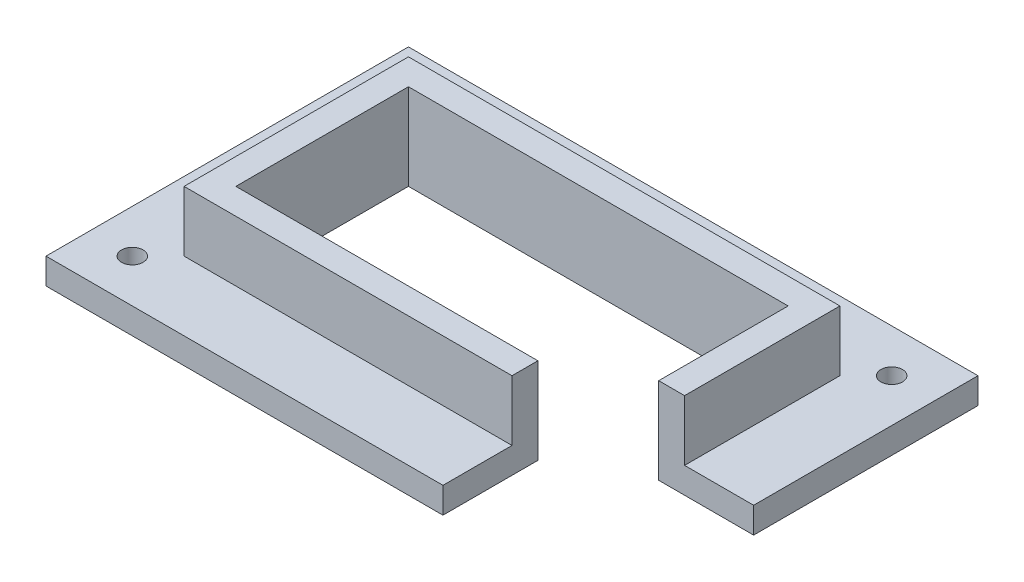
SolidWorks part; units mm, degrees
ref_plane "Front Plane" through (0, 0, 0) normal (0, 0, 1) x (1, 0, 0)
ref_plane "Top Plane" through (0, 0, 0) normal (0, 1, 0) x (1, 0, 0)
ref_plane "Right Plane" through (0, 0, 0) normal (1, 0, 0) x (0, 0, -1)
sketch "Sketch1" plane through (0, 0, 0) normal (0, 1, 0) x (1, 0, 0)
  line L0 (13, -10) -> (13, -21)
  line L1 (-33, -21) -> (13, -21)
  line L2 (-33, -21) -> (-33, 21)
  line L3 (-33, 21) -> (33, 21)
  line L4 (33, -5) -> (33, 21)
  line L5 (22, 10) -> (22, -5)
  line L7 (-22, -10) -> (13, -10)
  line L8 (-22, -10) -> (-22, 10)
  line L9 (-22, 10) -> (22, 10)
  line L15 (22, -5) -> (33, -5)
  point P0 (0, 0)
  point P6 (0, 0)
  point P10 (0, 0)
  point P13 (0, 0)
  point P16 (0, 21)
  point P17 (0, 0)
  point P18 (35, -23)
  point P19 (22, -23)
  point P20 (0, 0)
  point P21 (13, -23)
  point P22 (-35, -23)
  point P23 (-35, 23)
  point P24 (-22, 10)
  point P25 (35, 23)
  point P26 (0, 0)
  point P27 (0, 0)
  point P28 (0, 0)
  point P29 (35, -9.1499)
  point P30 (-33, 0)
  dimension "D1" = 11
  dimension "D2" = 44
  dimension "D3" = 35
  dimension "D4" = 20
  dimension "D5" = 11
  dimension "D6" = 11
  dimension "D7" = 15
extrude "base" add sketch "Sketch1" along normal blind 3
sketch "Sketch2" plane through (0, 3, 0) normal (0, 1, 0) x (1, 0, 0)
  line L0 (13, -10) -> (13, -13)
  line L1 (13, -21) -> (13, -10) construction
  line L2 (13, -13) -> (-25, -13)
  line L3 (-25, -13) -> (-25, 13)
  line L4 (-25, 13) -> (25, 13)
  line L5 (25, 13) -> (25, -5)
  line L6 (22, -5) -> (33, -5) construction
  line L7 (25, -5) -> (22, -5)
  line L8 (22, -5) -> (22, 10)
  line L9 (22, 10) -> (-22, 10)
  line L10 (-22, 10) -> (-22, -10)
  line L11 (-22, -10) -> (13, -10)
  line L12 (-25, 10) -> (-22, 10) construction
  line L13 (-22, 10) -> (-22, 13) construction
  point P20 (29.1916, 17.1916)
  dimension "D1" = 3
extrude "wall" add sketch "Sketch2" along normal blind 7
sketch "Sketch3" plane through (0, 3, 0) normal (0, 1, 0) x (1, 0, 0)
  line L0 (-33, -21) -> (13, -21) construction
  line L1 (-33, 21) -> (-33, -21) construction
  line L2 (33, 21) -> (-33, 21) construction
  line L3 (33, -5) -> (33, 21) construction
  circle A0 centre (-28, -16) radius 1.25
  circle A1 centre (-28, 16) radius 1.25
  circle A2 centre (28, 16) radius 1.25
  point P6 (0, 0)
  point P7 (0, 0)
  dimension "D1" = 2.5
  dimension "D2" = 5
  dimension "D3" = 5
  dimension "D4" = 5
  dimension "D5" = 5
extrude "bolt slots" cut sketch "Sketch3" against normal up to surface (3 mm away) up to face at (2.6, 0, 1)
equation "\"D6@Sketch1\"=\"D1@Sketch1\""
equation "\"D5@Sketch1\"=\"D1@Sketch1\""
equation "\"D2@Sketch3\"=\"D3@Sketch3\""
equation "\"D4@Sketch3\"=\"D3@Sketch3\""
equation "\"D5@Sketch3\"=\"D3@Sketch3\""
